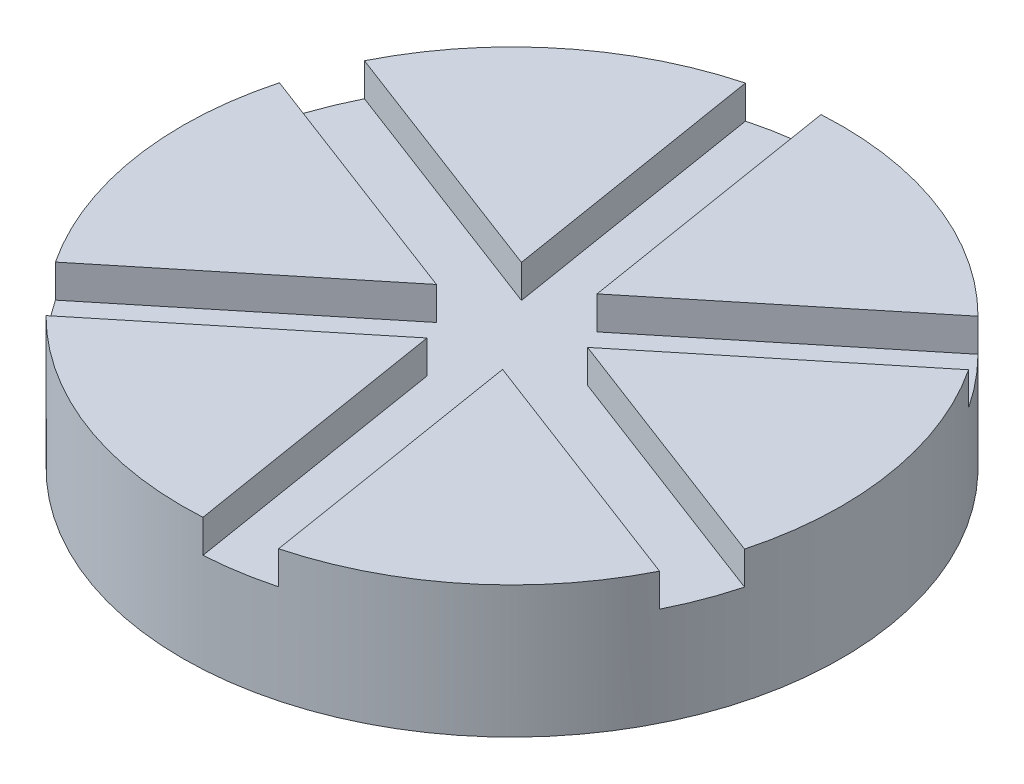
SolidWorks part; units mm, degrees
ref_plane "Front Plane" through (0, 0, 0) normal (0, 0, 1) x (1, 0, 0)
ref_plane "Top Plane" through (0, 0, 0) normal (0, 1, 0) x (1, 0, 0)
ref_plane "Right Plane" through (0, 0, 0) normal (1, 0, 0) x (0, 0, -1)
sketch "Sketch1" plane through (0, 0, 0) normal (0, 1, 0) x (1, 0, 0)
  circle A0 centre (0, 0) radius 127
  dimension "D1" = 254
extrude "Boss-Extrude1" add sketch "Sketch1" along normal blind 50.8
sketch "Sketch2" plane through (0, 50.8, 0) normal (0, 1, 0) x (1, 0, 0)
  line L0 (-90.3968, -90.1039) -> (-106.4491, -70.4193)
  line L1 (-98.423, -80.2616) -> (20.2971, -125.3676) construction
  line L2 (20.2971, -125.3676) -> (118.72, -45.106) construction
  line L3 (118.72, -45.106) -> (98.423, 80.2616) construction
  line L4 (98.423, 80.2616) -> (-20.2971, 125.3676) construction
  line L5 (-20.2971, 125.3676) -> (-118.72, 45.106) construction
  line L6 (-118.72, 45.106) -> (-98.423, -80.2616) construction
  line L7 (-114.2094, 56.978) -> (-123.2306, 33.234)
  line L8 (-7.7603, 127.3973) -> (-32.8338, 123.3379)
  line L9 (106.4491, 70.4193) -> (90.3968, 90.1039)
  line L10 (7.7603, -127.3973) -> (32.8338, -123.3379)
  line L11 (114.2094, -56.978) -> (123.2306, -33.234)
  line L12 (-123.2306, 33.234) -> (-25.0735, -4.0594)
  line L13 (-25.0735, -4.0594) -> (-106.4491, -70.4193)
  line L14 (-90.3968, -90.1039) -> (-9.0212, -23.744)
  line L15 (-25.0735, -4.0594) -> (-9.0212, -23.744) construction
  line L16 (-9.0212, -23.744) -> (16.0523, -19.6846) construction
  line L17 (16.0523, -19.6846) -> (25.0735, 4.0594) construction
  line L18 (25.0735, 4.0594) -> (9.0212, 23.744) construction
  line L19 (9.0212, 23.744) -> (-16.0523, 19.6846) construction
  line L20 (-16.0523, 19.6846) -> (-25.0735, -4.0594) construction
  line L21 (-9.0212, -23.744) -> (7.7603, -127.3973)
  line L22 (32.8338, -123.3379) -> (16.0523, -19.6846)
  line L23 (16.0523, -19.6846) -> (114.2094, -56.978)
  line L24 (123.2306, -33.234) -> (25.0735, 4.0594)
  line L25 (25.0735, 4.0594) -> (106.4491, 70.4193)
  line L26 (90.3968, 90.1039) -> (9.0212, 23.744)
  line L27 (-114.2094, 56.978) -> (-16.0523, 19.6846)
  line L28 (-16.0523, 19.6846) -> (-32.8338, 123.3379)
  line L29 (-7.7603, 127.3973) -> (9.0212, 23.744)
  circle A0 centre (0, 0) radius 109.9852 construction
  circle A1 centre (0, 0) radius 127 construction
  circle A2 centre (0, 0) radius 21.997 construction
  point P12 (-98.423, -80.2616)
  point P17 (-118.72, 45.106)
  point P20 (-20.2971, 125.3676)
  point P23 (98.423, 80.2616)
  point P26 (20.2971, -125.3676)
  point P29 (118.72, -45.106)
  dimension "D1" = 25.4
extrude "Cut-Extrude1" cut sketch "Sketch2" against normal blind 12.7
